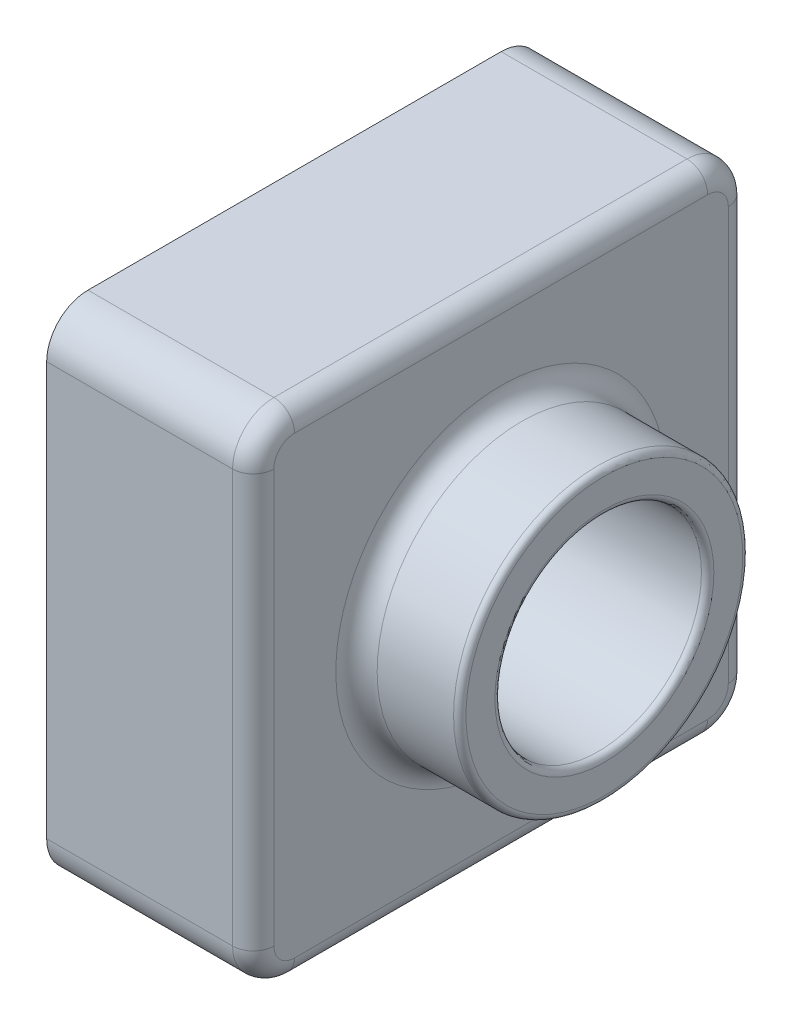
SolidWorks part; units mm, degrees
material "Plain Carbon Steel"
ref_plane "Front Plane" through (0, 0, 0) normal (0, 0, 1) x (1, 0, 0)
ref_plane "Top Plane" through (0, 0, 0) normal (0, 1, 0) x (1, 0, 0)
ref_plane "Right Plane" through (0, 0, 0) normal (1, 0, 0) x (0, 0, -1)
sketch "Sketch1" plane through (0, 0, 0) normal (1, 0, 0) x (0, 0, -1)
  line L1 (0, 0) -> (-120, 0)
  line L2 (0, 0) -> (0, 120)
  line L3 (0, 120) -> (-120, 120)
  line L4 (-120, 0) -> (-120, 120)
  dimension "D1" = 120
  dimension "D2" = 120
extrude "Boss-Extrude1" add sketch "Sketch1" along normal blind 50
sketch "Sketch2" plane through (50, 0, 0) normal (1, 0, 0) x (0, 0, -1)
  line L0 (0, 120) -> (-120, 120) construction
  line L1 (0, 0) -> (0, 120) construction
  circle A0 centre (-60, 60) radius 35
  dimension "D1" = 70
  dimension "D2" = 60
  dimension "D3" = 60
extrude "Boss-Extrude2" add sketch "Sketch2" along normal blind 25
sketch "Sketch3" plane through (75, 0, 0) normal (1, 0, 0) x (0, 0, -1)
  circle A0 centre (-60, 60) radius 25
  dimension "D1" = 50
extrude "Cut-Extrude1" cut sketch "Sketch3" against normal through all both and the other way through all
fillet "Fillet2" radius 10 4 edges at (25, 0, 0) (25, 0, 120) (25, 120, 120) (25, 120, 0)
fillet "Fillet3" radius 1.5 2 edges at (75, 60, 25)
fillet "Fillet5" radius 5 9 edges at (50, 2.9289, 117.0711) (50, 60, 120) (50, 117.0711, 117.0711) (50, 120, 60) (50, 117.0711, 2.9289) (50, 60, 0) (50, 2.9289, 2.9289) (50, 0, 60) (50, 60, 25)
shell "Shell1" thickness 2
